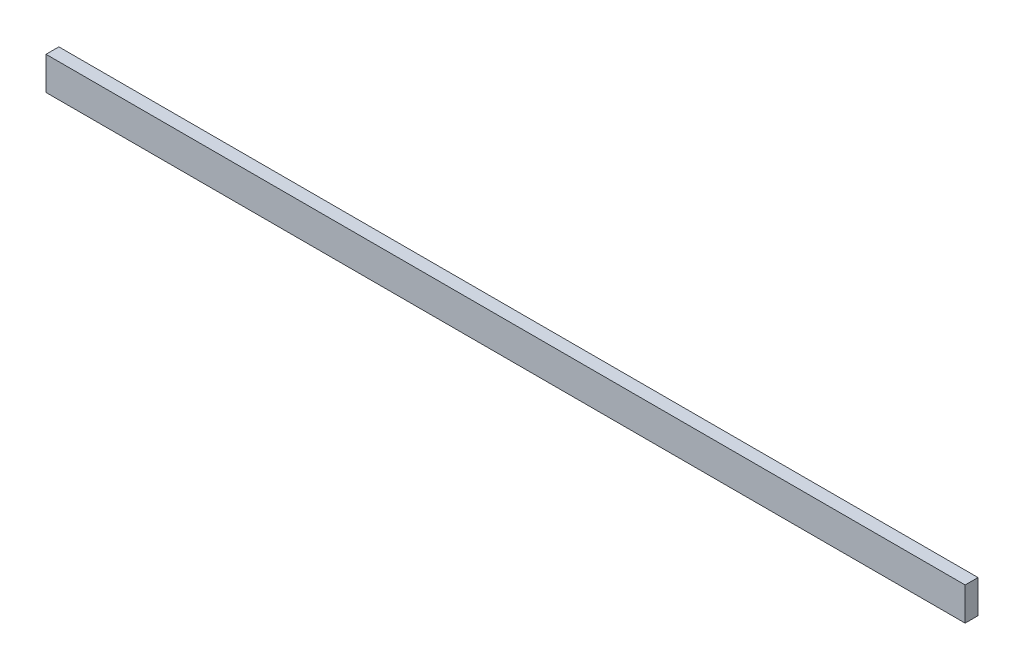
SolidWorks part; units mm, degrees
ref_plane "Front Plane" through (0, 0, 0) normal (0, 0, 1) x (1, 0, 0)
ref_plane "Top Plane" through (0, 0, 0) normal (0, 1, 0) x (1, 0, 0)
ref_plane "Right Plane" through (0, 0, 0) normal (1, 0, 0) x (0, 0, -1)
sketch "Sketch1" plane through (0, 0, 0) normal (0, 0, 1) x (1, 0, 0)
  line L1 (-38.9216, 24.4845) -> (596.0784, 24.4845)
  line L2 (-38.9216, 24.4845) -> (-38.9216, 1.6245)
  line L3 (-38.9216, 1.6245) -> (596.0784, 1.6245)
  line L4 (596.0784, 24.4845) -> (596.0784, 1.6245)
  dimension "D1" = 635
  dimension "D2" = 22.86
extrude "Boss-Extrude1" add sketch "Sketch1" along normal blind 8.89
